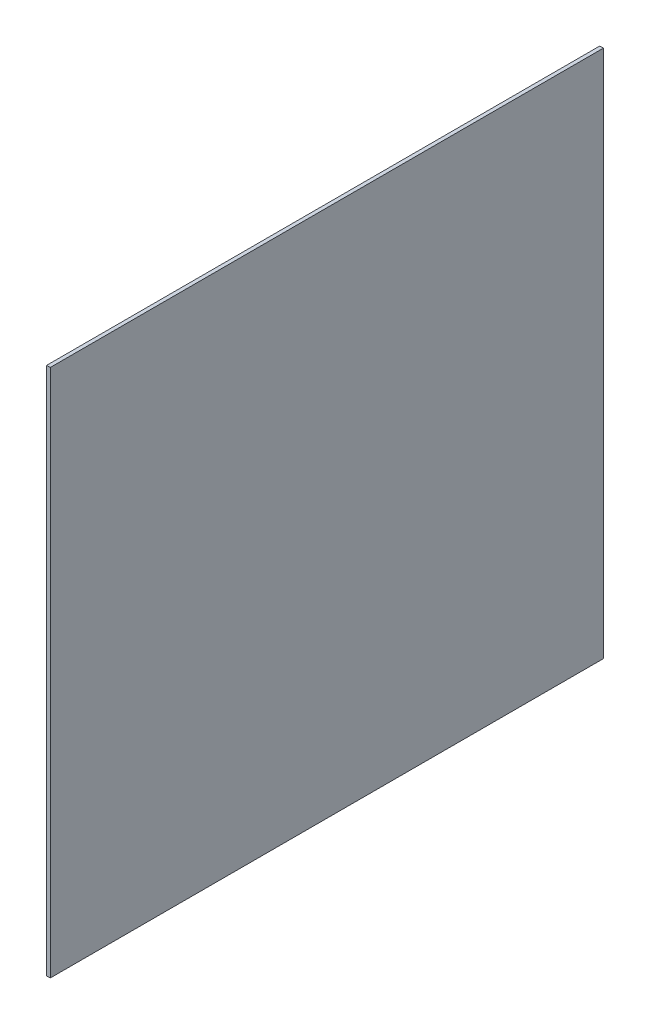
SolidWorks part; units mm, degrees
material "Acrylic (Medium-high impact)"
ref_plane "Top Plane" through (0, 0, 0) normal (0, 0, 1) x (1, 0, 0)
ref_plane "Front Plane" through (0, 0, 0) normal (0, 1, 0) x (1, 0, 0)
ref_plane "Right Plane" through (0, 0, 0) normal (1, 0, 0) x (0, 0, -1)
sketch "Sketch1" plane through (0, 0, 0) normal (1, 0, 0) x (0, 0, -1)
  line L1 (-227, 217) -> (227, 217)
  line L2 (-227, 217) -> (-227, -217)
  line L3 (-227, -217) -> (227, -217)
  line L4 (227, 217) -> (227, -217)
  line L5 (-227, 217) -> (227, -217) construction
  line L6 (-227, -217) -> (227, 217) construction
  point P0 (0, 0)
  dimension "D1" = 454
  dimension "D2" = 434
extrude "Boss-Extrude1" add sketch "Sketch1" along normal blind 3
